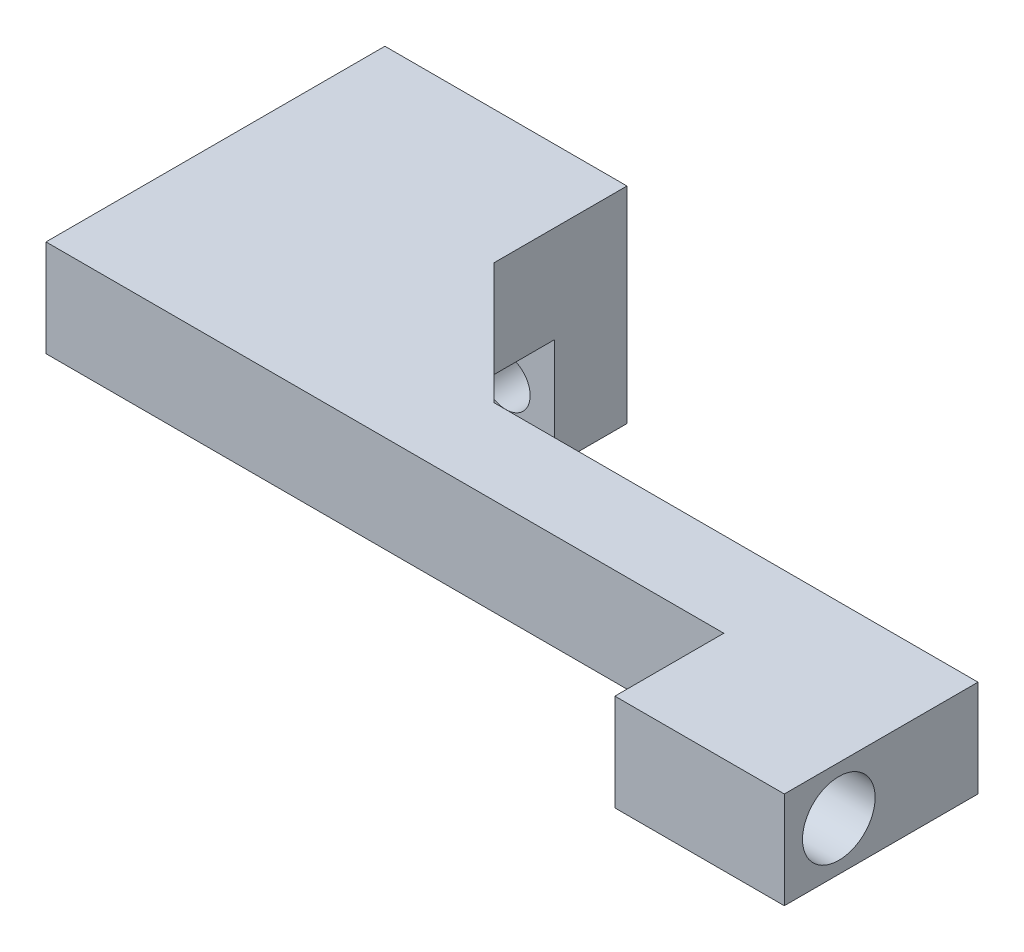
SolidWorks part; units mm, degrees
ref_plane "Front Plane" through (0, 0, 0) normal (0, 0, 1) x (1, 0, 0)
ref_plane "Top Plane" through (0, 0, 0) normal (0, 1, 0) x (1, 0, 0)
ref_plane "Right Plane" through (0, 0, 0) normal (1, 0, 0) x (0, 0, -1)
sketch "Sketch1" plane through (0, 0, 0) normal (0, 1, 0) x (1, 0, 0)
  line L0 (0, 0) -> (0, -28)
  line L1 (0, -28) -> (56, -28)
  line L2 (56, -28) -> (56, -37)
  line L3 (56, -37) -> (70, -37)
  line L4 (70, -37) -> (70, -21)
  line L5 (70, -21) -> (30, -21)
  line L6 (30, -21) -> (20, -11)
  line L7 (20, -11) -> (20, 0)
  line L8 (20, 0) -> (0, 0)
  dimension "D1" = 56
  dimension "D2" = 9
  dimension "D3" = 14
  dimension "D4" = 16
  dimension "D5" = 135
  dimension "D6" = 11
  dimension "D7" = 20
  dimension "D8" = 28
extrude "Boss-Extrude1" add sketch "Sketch1" against normal blind 8 contours L0 L1 L2 L3 L4 L5 L6 L7 L8
sketch "Sketch2" plane through (0, 0, 0) normal (-1, 0, 0) x (0, 0, 1)
  line L0 (0, -8) -> (0, -17)
  line L1 (0, -17) -> (6, -17)
  line L2 (6, -17) -> (6, -8)
  line L3 (0, -8) -> (28, -8) construction
  line L4 (0, -8) -> (6, -8)
  dimension "D1" = 9
  dimension "D2" = 6
extrude "Boss-Extrude2" add sketch "Sketch2" against normal blind 20 contours L2 L4 L0 L1
sketch "Sketch3" plane through (56, 0, 0) normal (-1, 0, 0) x (0, 0, 1)
  line L1 (28, -8) -> (28, 0) construction
  line L2 (28, -8) -> (37, -8) construction
  circle A0 centre (32.5, -4) radius 3
  dimension "D1" = 6
  dimension "D3" = 4
  dimension "D2" = 4.5
extrude "Cut-Extrude1" cut sketch "Sketch3" against normal up to next contours A0
sketch "Sketch4" plane through (0, 0, 6) normal (0, 0, 1) x (1, 0, 0)
  line L0 (0, -17) -> (0, -8) construction
  line L1 (20, -17) -> (0, -17) construction
  line L2 (20, -17) -> (20, -8) construction
  circle A0 centre (4, -13) radius 2
  circle A1 centre (16, -13) radius 2
  dimension "D2" = 4
  dimension "D4" = 4
  dimension "D1" = 4
  dimension "D3" = 4
  dimension "D5" = 4
  dimension "D6" = 4
extrude "Cut-Extrude2" cut sketch "Sketch4" against normal blind 10 contours A0 | A1
